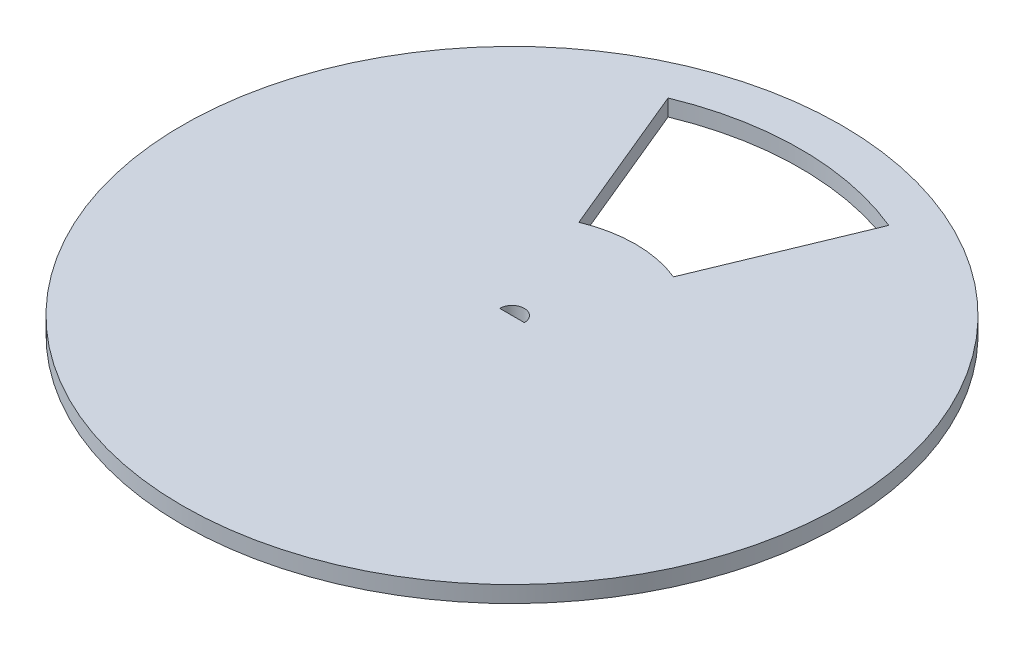
SolidWorks part; units mm, degrees
ref_plane "Front Plane" through (0, 0, 0) normal (0, 0, 1) x (1, 0, 0)
ref_plane "Top Plane" through (0, 0, 0) normal (0, 1, 0) x (1, 0, 0)
ref_plane "Right Plane" through (0, 0, 0) normal (1, 0, 0) x (0, 0, -1)
sketch "Sketch2" plane through (0, 0, 0) normal (0, 1, 0) x (1, 0, 0)
  circle A0 centre (0, 0) radius 40
  dimension "D1" = 80
extrude "Boss-Extrude1" add sketch "Sketch2" along normal blind 2 contours A0
sketch "Sketch3" plane through (0, 2, 0) normal (0, 1, 0) x (1, 0, 0)
  line L0 (13.3939, 32.3358) -> (-13.3939, 32.3358) construction
  line L1 (0, 0) -> (13.3939, 32.3358) construction
  line L2 (0, 0) -> (-13.3939, 32.3358) construction
  line L3 (-5.7403, 13.8582) -> (-13.3939, 32.3358)
  line L4 (13.3939, 32.3358) -> (5.7403, 13.8582)
  arc A0 (-13.3939, 32.3358) -> (13.3939, 32.3358) centre (0, 0) cw
  arc A1 (5.7403, 13.8582) -> (-5.7403, 13.8582) centre (0, 0) ccw
  point P4 (0, 32.3358)
  dimension "D3" = 15
  dimension "D1" = 35
  dimension "D2" = 45
extrude "Cut-Extrude1" cut sketch "Sketch3" against normal up to next
sketch "Sketch5" plane through (0, 2, 0) normal (0, 1, 0) x (1, 0, 0)
  line L0 (-1.5, 0) -> (1.5, 0)
  arc A1 (-1.5, 0) -> (1.5, 0) centre (0, 0) cw
  dimension "D1" = 1.5
extrude "Cut-Extrude2" cut sketch "Sketch5" against normal through all
